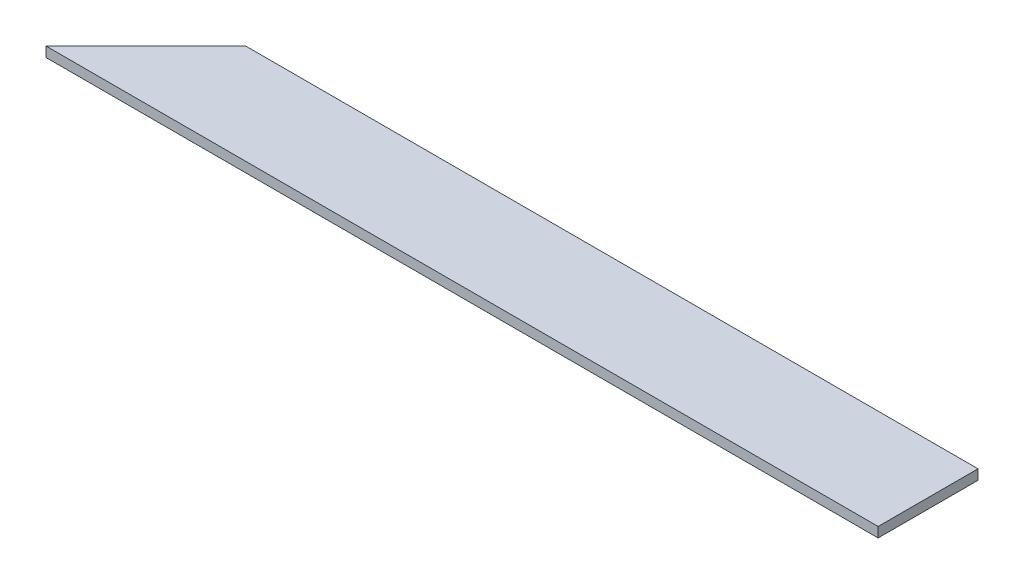
SolidWorks part; units mm, degrees
ref_plane "Front Plane" through (0, 0, 0) normal (0, 0, 1) x (1, 0, 0)
ref_plane "Top Plane" through (0, 0, 0) normal (0, 1, 0) x (1, 0, 0)
ref_plane "Right Plane" through (0, 0, 0) normal (1, 0, 0) x (0, 0, -1)
sketch "Sketch1" plane through (0, 0, 0) normal (0, 1, 0) x (1, 0, 0)
  line L0 (-125, -15) -> (-95, 15)
  line L1 (-125, 15) -> (125, 15) construction
  line L2 (-125, 15) -> (-125, -15) construction
  line L3 (-125, -15) -> (125, -15)
  line L4 (125, 15) -> (125, -15)
  line L5 (-125, 15) -> (125, -15) construction
  line L6 (-125, -15) -> (125, 15) construction
  line L7 (125, 15) -> (-95, 15)
  point P0 (0, 0)
  dimension "D1" = 45
  dimension "D2" = 250
  dimension "D3" = 30
extrude "Boss-Extrude2" add sketch "Sketch1" along normal blind 3
